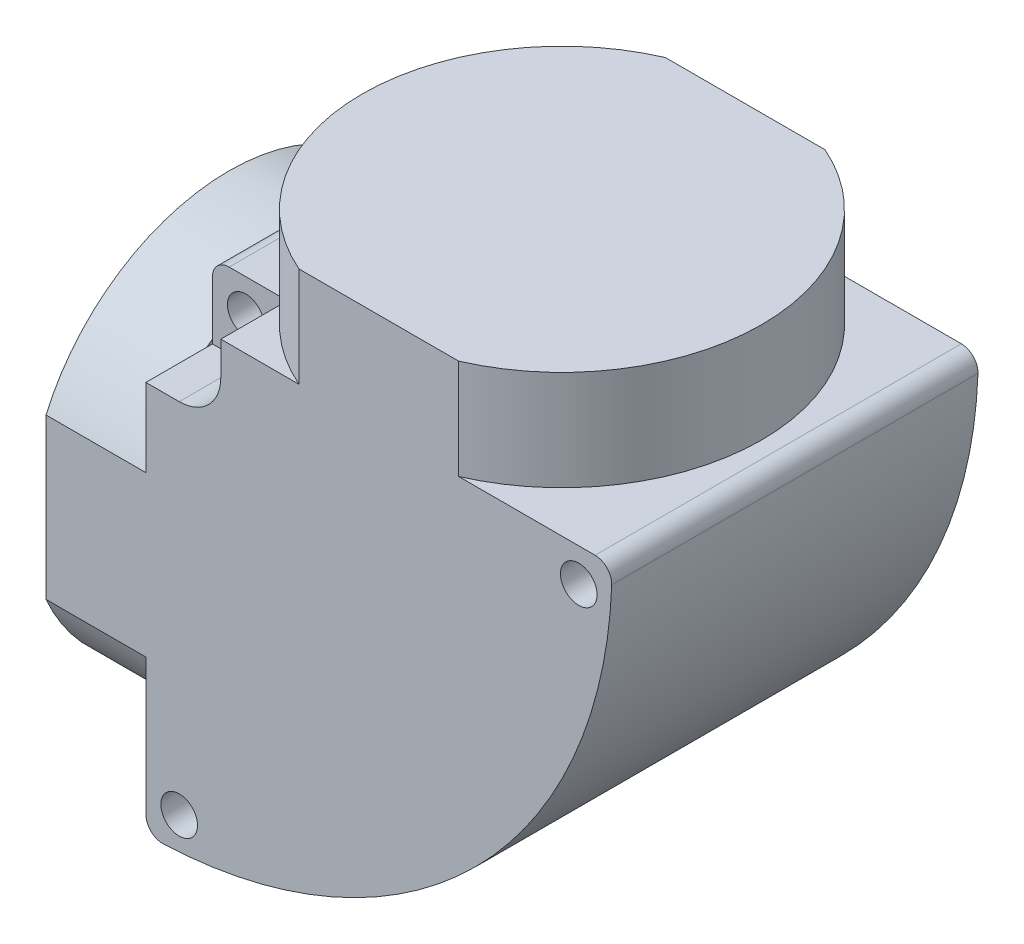
SolidWorks part; units mm, degrees
ref_plane "前视基准面" through (0, 0, 0) normal (0, 0, 1) x (1, 0, 0)
ref_plane "上视基准面" through (0, 0, 0) normal (0, 1, 0) x (1, 0, 0)
ref_plane "右视基准面" through (0, 0, 0) normal (1, 0, 0) x (0, 0, -1)
sketch "草图1" plane through (0, 0, 0) normal (0, 0, 1) x (1, 0, 0)
  line L0 (0, 0) -> (28, 0)
  line L1 (0, 0) -> (0, -28)
  arc A0 (28, 0) -> (0, -28) centre (0, 0) cw
  dimension "D1" = 28
  dimension "D2" = 28
extrude "凸台-拉伸1" add sketch "草图1" along normal blind 22
sketch "草图2" plane through (0, 0, 22) normal (0, 0, 1) x (1, 0, 0)
  line L0 (0, 0) -> (19.799, -19.799) construction
  line L1 (28, 0) -> (0, 0) construction
  line L2 (0, -2) -> (28.4628, -2) construction
  line L3 (0, 0) -> (0, -28) construction
  line L4 (2, -2) -> (2, -37.5585) construction
  arc A0 (0, -28) -> (28, 0) centre (0, 0) ccw construction
  circle A1 centre (2, -2) radius 1.1
  circle A2 centre (26, -2) radius 1.1
  circle A3 centre (2, -26) radius 1.1
  dimension "D1" = 2
  dimension "D2" = 2.2
  dimension "D3" = 24
  dimension "D4" = 2.2
extrude "切除-拉伸1" cut sketch "草图2" against normal blind 22
sketch "草图4" plane through (0, 0, 22) normal (0, 0, 1) x (1, 0, 0)
  line L0 (0, 0) -> (19.799, -19.799) construction
  line L1 (4.5, -2) -> (4.5, 0.5)
  line L8 (4.5, 0.5) -> (-2.8671, 0.5)
  line L9 (-2.8671, 0.5) -> (-2.8671, -4.5)
  line L10 (2, -4.5) -> (-2.8671, -4.5)
  arc A0 (0, -28) -> (28, 0) centre (0, 0) ccw construction
  arc A2 (2, -4.5) -> (4.5, -2) centre (2, -2) ccw
extrude "切除-拉伸2" cut sketch "草图4" against normal blind 4
fillet "圆角2" radius 1 3 edges at (0, 0, 9) (28, 0, 11) (0, -28, 11)
sketch "草图5" plane through (0, 0, 0) normal (-1, 0, 0) x (0, 0, 1)
  line L0 (0, -13.9907) -> (22, -13.9907) construction
  line L1 (0, -1) -> (0, -26.9815) construction
  line L2 (22, -4.5) -> (22, -26.9815) construction
  line L3 (11, -26.9815) -> (11, -1) construction
  line L4 (0, -26.9815) -> (22, -26.9815) construction
  line L5 (18, -1) -> (0, -1) construction
  line L6 (0, -9.1949) -> (0, -18.7866)
  line L7 (22, -9.1949) -> (22, -18.7866)
  arc A0 (0, -18.7866) -> (22, -18.7866) centre (11, -13.9907) ccw
  arc A1 (22, -9.1949) -> (0, -9.1949) centre (11, -13.9907) ccw
  dimension "D1" = 12
extrude "凸台-拉伸2" add sketch "草图5" along normal blind 6
sketch "草图6" plane through (0, 0, 0) normal (0, 1, 0) x (1, 0, 0)
  line L0 (13.9907, 0) -> (13.9907, -22) construction
  line L1 (26.9815, 0) -> (1, 0) construction
  line L2 (26.9815, -22) -> (4.5, -22) construction
  line L3 (26.9815, -11) -> (1, -11) construction
  line L4 (26.9815, -22) -> (26.9815, 0) construction
  line L5 (1, 0) -> (1, -18) construction
  line L6 (9.1949, 0) -> (18.7866, 0)
  line L7 (9.1949, -22) -> (18.7866, -22)
  arc A0 (9.1949, 0) -> (9.1949, -22) centre (13.9907, -11) ccw
  arc A1 (18.7866, -22) -> (18.7866, 0) centre (13.9907, -11) ccw
  dimension "D1" = 24
extrude "凸台-拉伸3" add sketch "草图6" along normal blind 6
